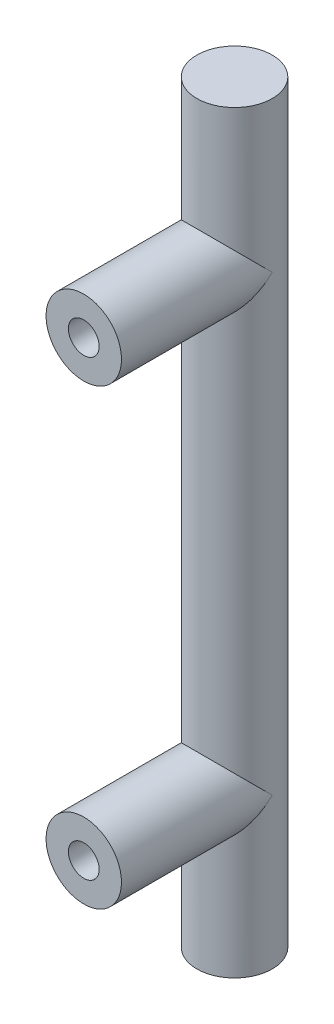
SolidWorks part; units mm, degrees
ref_plane "Front Plane" through (0, 0, 0) normal (0, 0, 1) x (1, 0, 0)
ref_plane "Top Plane" through (0, 0, 0) normal (0, 1, 0) x (1, 0, 0)
ref_plane "Right Plane" through (0, 0, 0) normal (1, 0, 0) x (0, 0, -1)
sketch "Sketch2" plane through (0, 0, 0) normal (0, 1, 0) x (1, 0, 0)
  circle A0 centre (0, 0) radius 6.35
  dimension "D1" = 12.7
extrude "Boss-Extrude1" add sketch "Sketch2" along normal blind 127
sketch "Sketch3" plane through (0, 0, 0) normal (0, 0, 1) x (1, 0, 0)
  line L0 (0, 0) -> (0, 127) construction
  line L1 (6.35, 127) -> (-6.35, 127) construction
  line L3 (0, 101.6467) -> (0, 63.5) construction
  line L4 (0, 63.5) -> (0, 25.3533) construction
  circle A0 centre (0, 101.6467) radius 6.35
  circle A1 centre (0, 25.3533) radius 6.35
  dimension "D2" = 12.7
  dimension "D1" = 76.2933
extrude "Boss-Extrude2" add sketch "Sketch3" along normal blind 25.4
hole_wizard "#6 (0.204) Diameter Hole1" positions "Sketch4" profile "Sketch5" hole size "#6" standard "ANSI Inch"
sketch "Sketch4" plane through (0, 0, 25.4) normal (0, 0, 1) x (1, 0, 0)
  circle A0 centre (0, 101.6467) radius 6.35 construction
  circle A1 centre (0, 25.3533) radius 6.35 construction
  circle A2 centre (0, 101.6467) radius 6.35
  circle A3 centre (0, 25.3533) radius 6.35
  point P1 (0, 101.6467)
  point P3 (0, 25.3533)
sketch "Sketch5" plane through (0, 101.6467, 25.4) normal (1, 0, 0) x (0, -1, 0)
  line L0 (0, 0) -> (0, 14.2567)
  line L1 (0, 14.2567) -> (2.5908, 12.7)
  line L2 (2.5908, 12.7) -> (2.5908, 0)
  line L5 (2.5908, 0) -> (0, 0)
  line L10 (0, 14.2567) -> (-2.5908, 12.7) construction
  line L11 (0, -6.35) -> (0, 107.95) construction
  dimension "Hole Dia." = 5.1816
  dimension "Hole Depth" = 12.7
  dimension "Drill Angle" = 118
